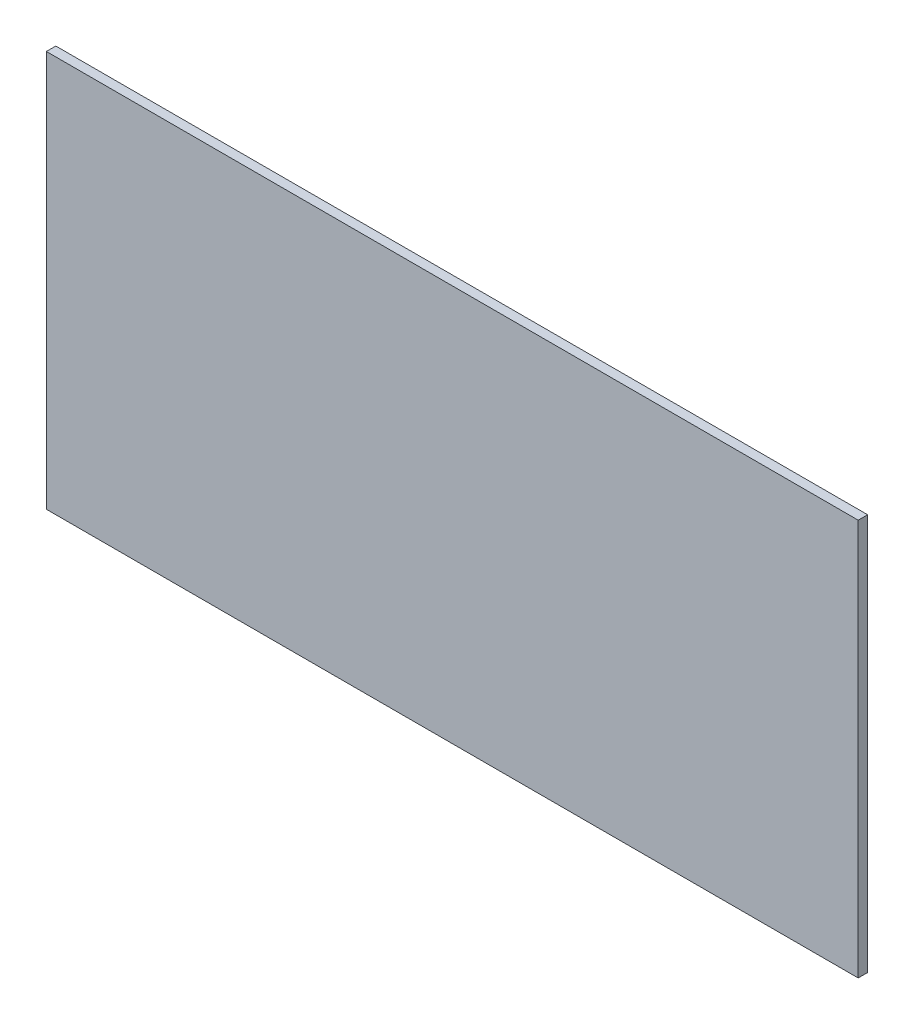
SolidWorks part; units mm, degrees
ref_plane "Alzado" through (0, 0, 0) normal (0, 0, 1) x (1, 0, 0)
ref_plane "Planta" through (0, 0, 0) normal (0, 1, 0) x (1, 0, 0)
ref_plane "Vista lateral" through (0, 0, 0) normal (1, 0, 0) x (0, 0, -1)
sketch "Croquis1" plane through (0, 0, 0) normal (0, 0, 1) x (1, 0, 0)
  line L1 (0, 0) -> (409.525, 0)
  line L2 (0, 0) -> (0, 200)
  line L3 (0, 200) -> (409.525, 200)
  line L4 (409.525, 0) -> (409.525, 200)
  dimension "D1" = 200
  dimension "D2" = 409.525
extrude "Saliente-Extruir5" add sketch "Croquis1" along normal blind 4.7625
